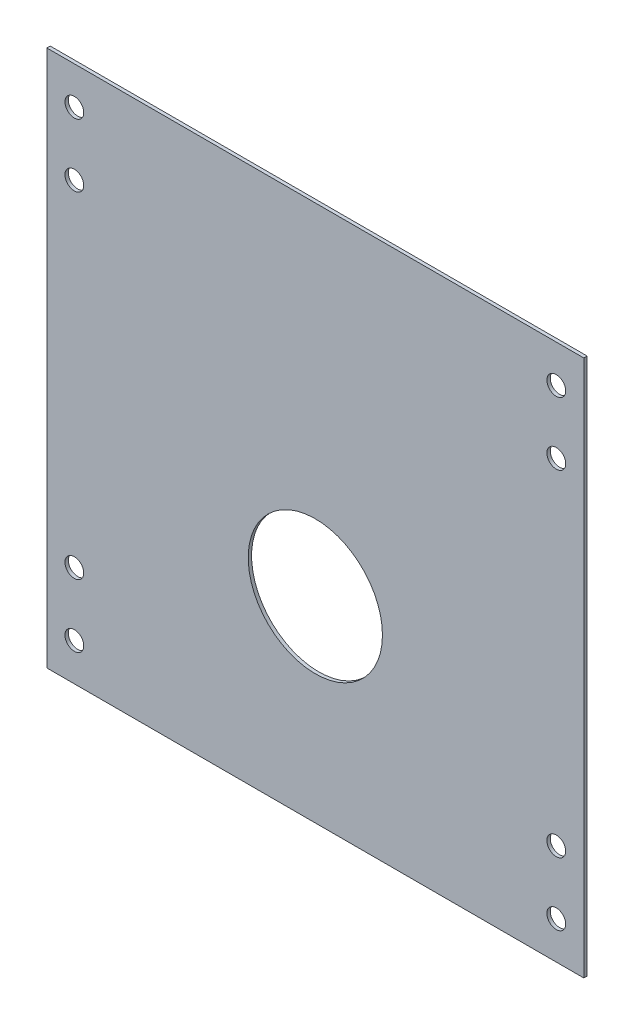
SolidWorks part; units mm, degrees
ref_plane "前视基准面" through (0, 0, 0) normal (0, 0, 1) x (1, 0, 0)
ref_plane "上视基准面" through (0, 0, 0) normal (0, 1, 0) x (1, 0, 0)
ref_plane "右视基准面" through (0, 0, 0) normal (1, 0, 0) x (0, 0, -1)
sketch "草图2" plane through (0, 0, 0) normal (0, 0, 1) x (1, 0, 0)
  line L0 (0, -203.2) -> (0, -54.602) construction
  line L1 (-203.2, 203.2) -> (203.2, 203.2)
  line L2 (-203.2, 203.2) -> (-203.2, -203.2)
  line L3 (-203.2, -203.2) -> (203.2, -203.2)
  line L4 (203.2, 203.2) -> (203.2, -203.2)
  line L5 (0, -54.602) -> (-203.2, -54.602) construction
  line L6 (0, -54.602) -> (203.2, -54.602) construction
  circle A0 centre (0, -54.602) radius 50.8
  dimension "D1" = 148.598
  dimension "D2" = 406.4
  dimension "D4" = 406.4
sketch "草图3" plane through (0, 0, 0) normal (0, 0, 1) x (1, 0, 0)
  line L0 (0, 203.2) -> (0, -203.2) construction
  line L2 (-203.2, 174.752) -> (-182.372, 174.752) construction
  line L5 (-182.372, 174.752) -> (-182.372, 203.2) construction
  line L6 (-182.372, 174.752) -> (-182.372, 127) construction
  line L7 (0, 0) -> (-203.2, 0) construction
  line L8 (0, 0) -> (203.2, 0) construction
  circle A0 centre (-182.372, 174.752) radius 7.112
  circle A1 centre (-182.372, 127) radius 7.112
  circle A2 centre (182.372, 127) radius 7.112
  circle A3 centre (182.372, 174.752) radius 7.112
  circle A4 centre (182.372, -174.752) radius 7.112
  circle A5 centre (182.372, -127) radius 7.112
  circle A6 centre (-182.372, -174.752) radius 7.112
  circle A7 centre (-182.372, -127) radius 7.112
  dimension "D1" = 28.448
  dimension "D2" = 20.828
  dimension "D3" = 47.752
extrude "凸台-拉伸1" add sketch "草图2" along normal blind 2.54
sketch "草图4" plane through (0, 0, 0) normal (0, 0, 1) x (1, 0, 0)
  line L0 (0, 199.5734) -> (0, -203.2) construction
  line L1 (0, 203.2) -> (0, -203.2) construction
  line L2 (-203.2, 0) -> (203.2, 0) construction
  circle A0 centre (-182.372, 127) radius 7.112
  circle A1 centre (-182.372, 174.752) radius 7.112
  circle A2 centre (-182.372, -174.752) radius 7.112
  circle A3 centre (-182.372, -127) radius 7.112
  circle A4 centre (182.372, -127) radius 7.112
  circle A5 centre (182.372, -174.752) radius 7.112
  circle A6 centre (182.372, 174.752) radius 7.112
  circle A7 centre (182.372, 127) radius 7.112
extrude "切除-拉伸4" cut sketch "草图4" along normal through all
